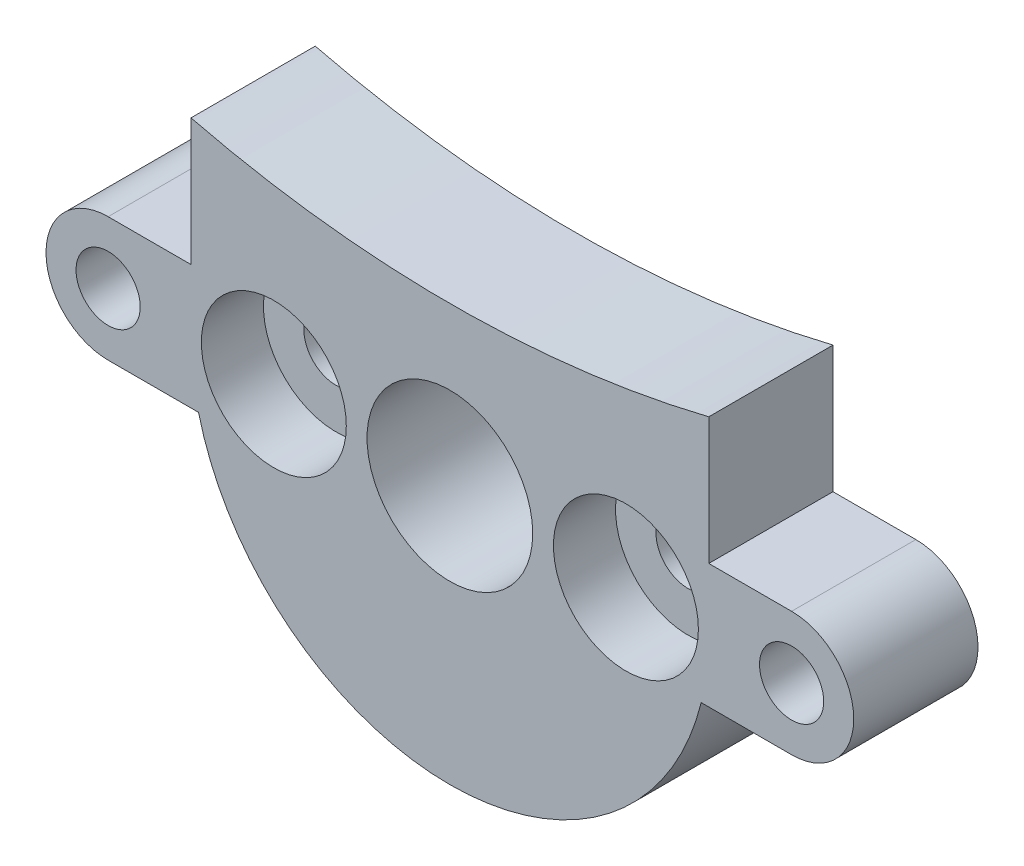
SolidWorks part; units mm, degrees
ref_plane "Front Plane" through (0, 0, 0) normal (0, 0, 1) x (1, 0, 0)
ref_plane "Top Plane" through (0, 0, 0) normal (0, 1, 0) x (1, 0, 0)
ref_plane "Right Plane" through (0, 0, 0) normal (1, 0, 0) x (0, 0, -1)
sketch "Sketch1" plane through (0, 0, 0) normal (0, 0, 1) x (1, 0, 0)
  line L0 (-8.5, 0) -> (8.5, 0) construction
  line L1 (0, 0) -> (0, 60) construction
  line L6 (-8.5, 0) -> (-16.5, 0) construction
  line L7 (8.5, 0) -> (16.5, 0) construction
  line L8 (-16.5, 3) -> (-12.5, 3)
  line L10 (16.5, 3) -> (12.5, 3)
  line L12 (-12.5, 9.1325) -> (-12.5, 3)
  line L13 (12.5, 3) -> (12.5, 9.1325)
  line L14 (16.5, -3) -> (12.1347, -3)
  line L15 (-16.5, -3) -> (-12.1347, -3)
  circle A0 centre (-8.5, 0) radius 1.55
  circle A1 centre (8.5, 0) radius 1.55
  circle A4 centre (0, 60) radius 52.3808 construction
  circle A8 centre (0, 0) radius 4
  arc A16 (-12.5, 0) -> (12.5, 0) centre (0, 0) ccw construction
  arc A17 (-12.5, 9.1325) -> (12.5, 9.1325) centre (0, 60) ccw
  circle A18 centre (-16.5, 0) radius 1.55
  circle A19 centre (16.5, 0) radius 1.55
  arc A21 (-16.5, 3) -> (-16.5, -3) centre (-16.5, 0) ccw
  arc A24 (16.5, 3) -> (16.5, -3) centre (16.5, 0) cw
  arc A25 (-12.1347, -3) -> (12.1347, -3) centre (0, 0) ccw
  point P4 (0, 0)
  point P13 (0, 7.6192)
  point P28 (0, 0)
extrude "Boss-Extrude1" add sketch "Sketch1" along normal blind 6
sketch "Sketch2" plane through (0, 0, 6) normal (0, 0, 1) x (1, 0, 0)
  circle A0 centre (-8.5, 0) radius 3.5
  circle A1 centre (8.5, 0) radius 3.5
extrude "Cut-Extrude1" cut sketch "Sketch2" against normal blind 3
